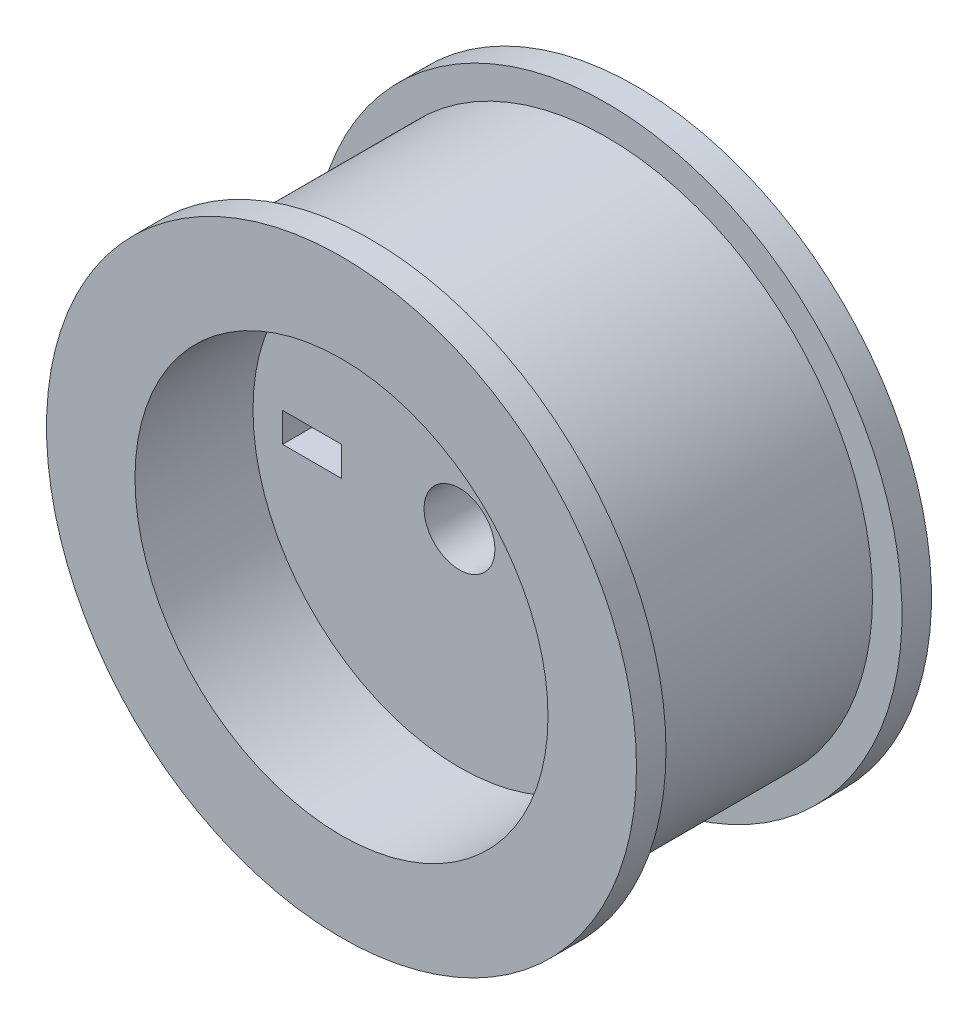
SolidWorks part; units mm, degrees
material "Nylon 6/10"
ref_plane "Front Plane" through (0, 0, 0) normal (0, 0, 1) x (1, 0, 0)
ref_plane "Top Plane" through (0, 0, 0) normal (0, 1, 0) x (1, 0, 0)
ref_plane "Right Plane" through (0, 0, 0) normal (1, 0, 0) x (0, 0, -1)
sketch "Sketch1" plane through (0, 0, 0) normal (0, 0, 1) x (1, 0, 0)
  circle A0 centre (0, 0) radius 45
extrude "Boss-Extrude1" add sketch "Sketch1" along normal blind 40
sketch "Sketch2" plane through (0, 0, 40) normal (0, 0, 1) x (1, 0, 0)
  circle A1 centre (0, 0) radius 50
extrude "Boss-Extrude2" add sketch "Sketch2" along normal blind 5
sketch "Sketch3" plane through (0, 0, 0) normal (0, 0, -1) x (-1, 0, 0)
  circle A0 centre (0, 0) radius 50
extrude "Boss-Extrude3" add sketch "Sketch3" along normal blind 5
sketch "Sketch4" plane through (0, 0, 45) normal (0, 0, 1) x (1, 0, 0)
  circle A0 centre (0, 0) radius 35
extrude "Cut-Extrude1" cut sketch "Sketch4" against normal blind 20
sketch "Sketch5" plane through (0, 0, -5) normal (0, 0, -1) x (-1, 0, 0)
  circle A0 centre (0, 0) radius 35
extrude "Cut-Extrude2" cut sketch "Sketch5" against normal blind 20
sketch "Sketch6" plane through (0, 0, 25) normal (0, 0, 1) x (1, 0, 0)
  circle A0 centre (0, 0) radius 6
extrude "Cut-Extrude3" cut sketch "Sketch6" against normal blind 20
sketch "Sketch7" plane through (0, 0, 25) normal (0, 0, 1) x (1, 0, 0)
  line L10 (-20, -0.0731) -> (-20, -2.5731)
  line L11 (-20, -2.5731) -> (-30, -2.5731)
  line L12 (-30, -0.0731) -> (-30, -2.5731)
  line L14 (-20, -0.0731) -> (-20, 2.4269)
  line L15 (-20, 2.4269) -> (-30, 2.4269)
  line L16 (-30, -0.0731) -> (-30, 2.4269)
  circle A0 centre (0, 0) radius 6 construction
  dimension "D4" = 20
  dimension "D1" = 10
  dimension "D2" = 2.5
  dimension "D3" = 2.5
extrude "Cut-Extrude4" cut sketch "Sketch7" against normal blind 10
